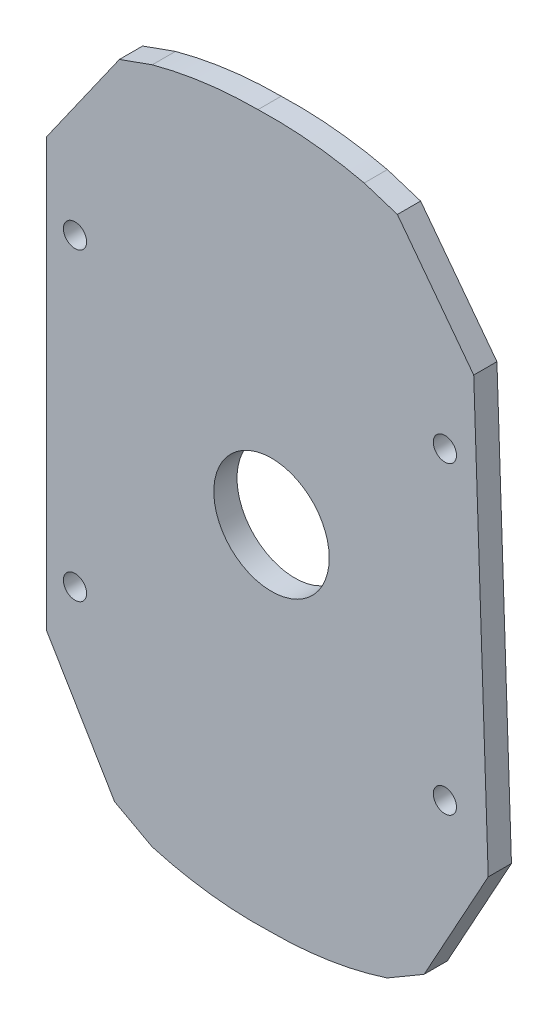
SolidWorks part; units mm, degrees
ref_plane "Front Plane" through (0, 0, 0) normal (0, 0, 1) x (1, 0, 0)
ref_plane "Top Plane" through (0, 0, 0) normal (0, 1, 0) x (1, 0, 0)
ref_plane "Right Plane" through (0, 0, 0) normal (1, 0, 0) x (0, 0, -1)
sketch "Sketch2" plane through (0, 0, 0) normal (0, 0, 1) x (1, 0, 0)
  line L0 (116.2517, 156.3536) -> (112.0061, 154.8342)
  line L1 (102.5908, 141.4647) -> (102.5908, 86.2136)
  line L2 (111.3851, 71.4533) -> (116.2517, 68.8189)
  line L4 (143.634, 156.8186) -> (147.9287, 155.4442)
  line L5 (157.7925, 142.4021) -> (159.6685, 87.1829)
  line L6 (151.3804, 72.1324) -> (146.6061, 69.3344)
  line L7 (112.0061, 154.8342) -> (102.5908, 141.4647)
  line L8 (147.9287, 155.4442) -> (157.7925, 142.4021)
  line L9 (102.5908, 86.2136) -> (111.3851, 71.4533)
  line L10 (159.6685, 87.1829) -> (151.3804, 72.1324)
  arc A0 (116.2517, 156.3536) -> (129.9159, 158.1721) centre (129.9159, 105.9281) cw
  arc A1 (143.634, 156.8186) -> (129.9159, 158.1721) centre (131.6898, 105.9582) ccw
  arc A4 (116.2517, 68.8189) -> (131.4647, 66.9692) centre (129.6439, 115.4776) ccw
  arc A6 (146.6061, 69.3344) -> (131.4647, 66.9692) centre (131.6373, 115.5115) cw
extrude "Boss-Extrude2" add sketch "Sketch2" along normal blind 3
sketch "Sketch3" plane through (0, 0, 3) normal (0, 0, 1) x (1, 0, 0)
  circle A0 centre (106.2708, 132.2947) radius 1.5
  circle A1 centre (106.2708, 92.9436) radius 1.5
  circle A2 centre (154.0659, 132.2947) radius 1.5
  circle A3 centre (154.0659, 92.9436) radius 1.5
  circle A6 centre (131.6636, 112.5856) radius 7.46
extrude "Cut-Extrude1" cut sketch "Sketch3" against normal blind 3
